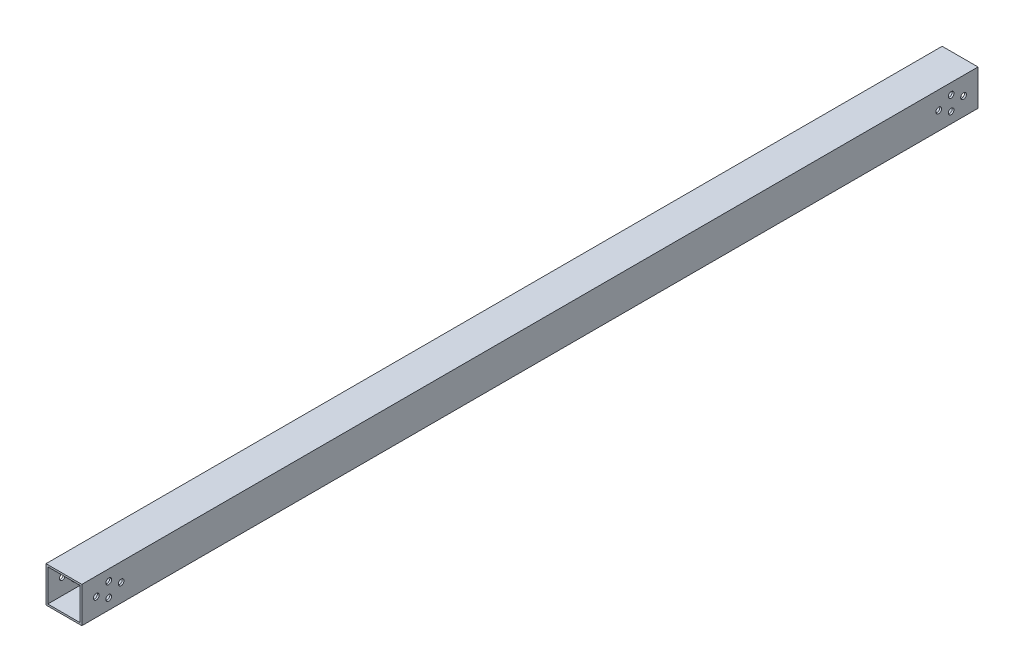
SolidWorks part; units mm, degrees
ref_plane "前视基准面" through (0, 0, 0) normal (0, 0, 1) x (1, 0, 0)
ref_plane "上视基准面" through (0, 0, 0) normal (0, 1, 0) x (1, 0, 0)
ref_plane "右视基准面" through (0, 0, 0) normal (1, 0, 0) x (0, 0, -1)
other "Configuration Table"
sketch "草图1" plane through (0, 0, 0) normal (0, 0, 1) x (1, 0, 0)
  line L1 (10, -10) -> (-10, -10)
  line L2 (10, -10) -> (10, 10)
  line L3 (10, 10) -> (-10, 10)
  line L4 (-10, -10) -> (-10, 10)
  line L5 (10, -10) -> (-10, 10) construction
  line L6 (10, 10) -> (-10, -10) construction
  line L7 (9, -9) -> (-9, -9)
  line L8 (9, -9) -> (9, 9)
  line L9 (9, 9) -> (-9, 9)
  line L10 (-9, -9) -> (-9, 9)
  line L11 (9, -9) -> (-9, 9) construction
  line L12 (9, 9) -> (-9, -9) construction
  point P0 (0, 0)
  point P6 (0, 0)
  dimension "D1" = 20
  dimension "D2" = 20
  dimension "D3" = 18
extrude "凸台-拉伸1" add sketch "草图1" along normal blind 500
sketch "草图2" plane through (-10, 0, 0) normal (-1, 0, 0) x (0, 0, 1)
  line L0 (0, 0) -> (62.4444, 0) construction
  line L8 (250, 10) -> (250, 13.1858) construction
  line L9 (500, 10) -> (0, 10) construction
  line L10 (0, 10) -> (0, -10) construction
  circle A0 centre (15, -4) radius 1.6
  circle A1 centre (15, 4) radius 1.6
  circle A2 centre (8.0718, 0) radius 1.6
  circle A3 centre (21.9282, 0) radius 1.6
  circle A4 centre (478.0718, 0) radius 1.6
  circle A5 centre (485, 4) radius 1.6
  circle A6 centre (485, -4) radius 1.6
  circle A7 centre (491.9282, 0) radius 1.6
  point P7 (250, 10)
  dimension "D1" = 3.2
  dimension "D2" = 8
  dimension "D3" = 15
  dimension "D4" = 8
  dimension "D5" = 8
extrude "切除-拉伸1" cut sketch "草图2" against normal up to surface (20 mm away) up to face at (10, 0, 250)
